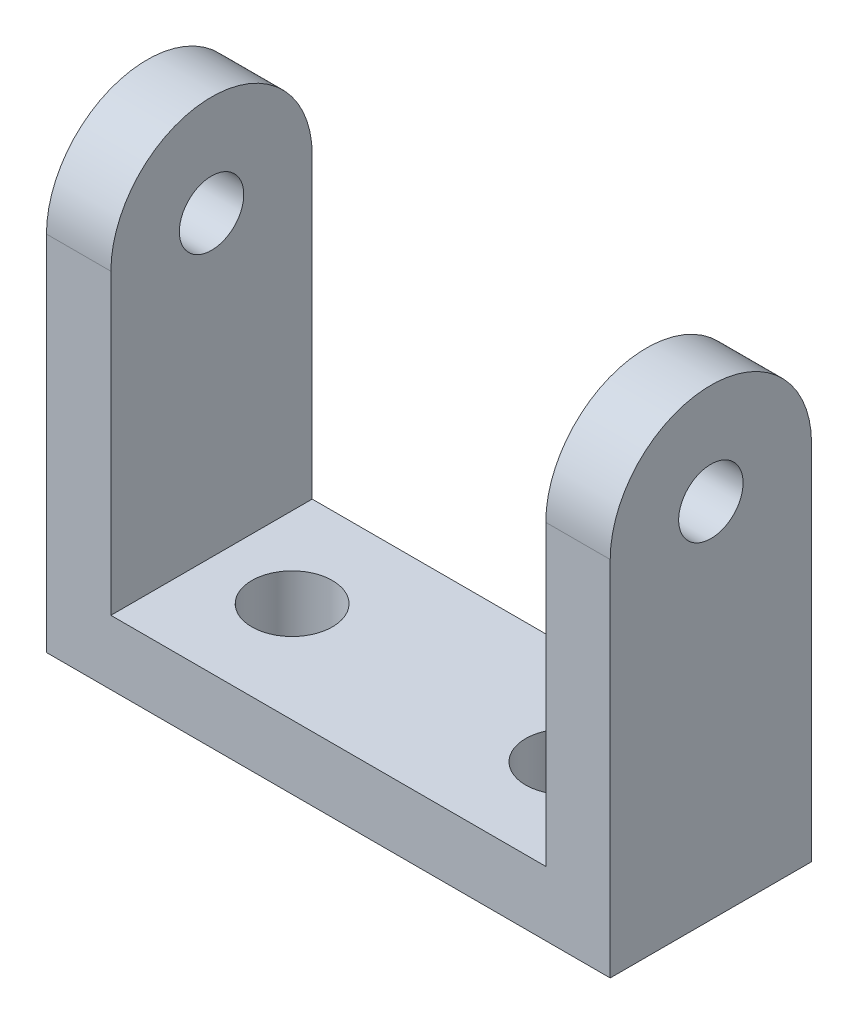
SolidWorks part; units mm, degrees
ref_plane "Front Plane" through (0, 0, 0) normal (0, 0, 1) x (1, 0, 0)
ref_plane "Top Plane" through (0, 0, 0) normal (0, 1, 0) x (1, 0, 0)
ref_plane "Right Plane" through (0, 0, 0) normal (1, 0, 0) x (0, 0, -1)
sketch "Sketch1" plane through (0, 0, 0) normal (0, 0, 1) x (1, 0, 0)
  line L0 (0, 0) -> (0, 52.9774) construction
  line L1 (0, 0) -> (35, 0)
  line L2 (35, 0) -> (35, 45)
  line L3 (0, 8) -> (27, 8)
  line L4 (27, 8) -> (27, 45)
  line L6 (35, 45) -> (27, 45)
  line L7 (0, 8) -> (-27, 8)
  line L8 (0, 0) -> (-35, 0)
  line L9 (-35, 45) -> (-27, 45)
  line L10 (-27, 8) -> (-27, 45)
  line L11 (-35, 0) -> (-35, 45)
  dimension "D1" = 45
  dimension "D2" = 35
  dimension "D3" = 8
extrude "Boss-Extrude1" add sketch "Sketch1" along normal blind 25
sketch "Sketch2" plane through (35, 0, 0) normal (1, 0, 0) x (0, 0, -1)
  line L0 (-25, 45) -> (0, 45) construction
  line L1 (-25, 45) -> (0, 45)
  arc A0 (-25, 45) -> (0, 45) centre (-12.5, 45) cw
  line M2 (0, 45) -> (-25, 45)
extrude "Boss-Extrude2" add sketch "Sketch2" against normal up to surface (62 mm away) contours A0 M2
sketch "Sketch3" plane through (35, 0, 0) normal (1, 0, 0) x (0, 0, -1)
  line L0 (-25, 45) -> (0, 45)
  arc A0 (0, 45) -> (-25, 45) centre (-12.5, 45) ccw construction
  arc A1 (0, 45) -> (-25, 45) centre (-12.5, 45) ccw
  circle A2 centre (-12.5, 45) radius 4
  dimension "D1" = 8
extrude "Cut-Extrude1" cut sketch "Sketch3" against normal up to surface (8 mm away) contours L0 A2 | L0 A2 up to face at (27, 29.625, 12.5)
sketch "Sketch4" plane through (-35, 0, 0) normal (-1, 0, 0) x (0, 0, 1)
  line L0 (25, 45) -> (0, 45) construction
  line L1 (25, 45) -> (0, 45)
  arc A0 (0, 45) -> (25, 45) centre (12.5, 45) cw
  line M4 (25, 45) -> (0, 45)
extrude "Boss-Extrude3" add sketch "Sketch4" against normal up to surface (8 mm away) contours A0 M4 up to face at (-27, 26.5, 12.5)
sketch "Sketch5" plane through (-35, 0, 0) normal (-1, 0, 0) x (0, 0, 1)
  line L0 (0, 45) -> (25, 45)
  arc A0 (25, 45) -> (0, 45) centre (12.5, 45) ccw construction
  arc A1 (25, 45) -> (0, 45) centre (12.5, 45) ccw
  circle A2 centre (12.5, 45) radius 4
  dimension "D1" = 8
extrude "Cut-Extrude2" cut sketch "Sketch5" against normal up to surface (8 mm away) contours L0 A2 | L0 A2 up to face at (-27, 29.625, 12.5)
sketch "Sketch6" plane through (0, 8, 0) normal (0, 1, 0) x (1, 0, 0)
  line L0 (27, 0) -> (-27, 0) construction
  line L2 (27, 0) -> (-27, 0)
  line L3 (0, 0) -> (0, -25)
  line L4 (27, -25) -> (-27, -25) construction
  line L5 (17, -12.5) -> (-17, -12.5)
  circle A0 centre (-17, -12.5) radius 5
  circle A1 centre (17, -12.5) radius 5
  point P9 (0, -12.5)
  dimension "D2" = 10
  dimension "D1" = 17
extrude "Cut-Extrude3" cut sketch "Sketch6" against normal through all
